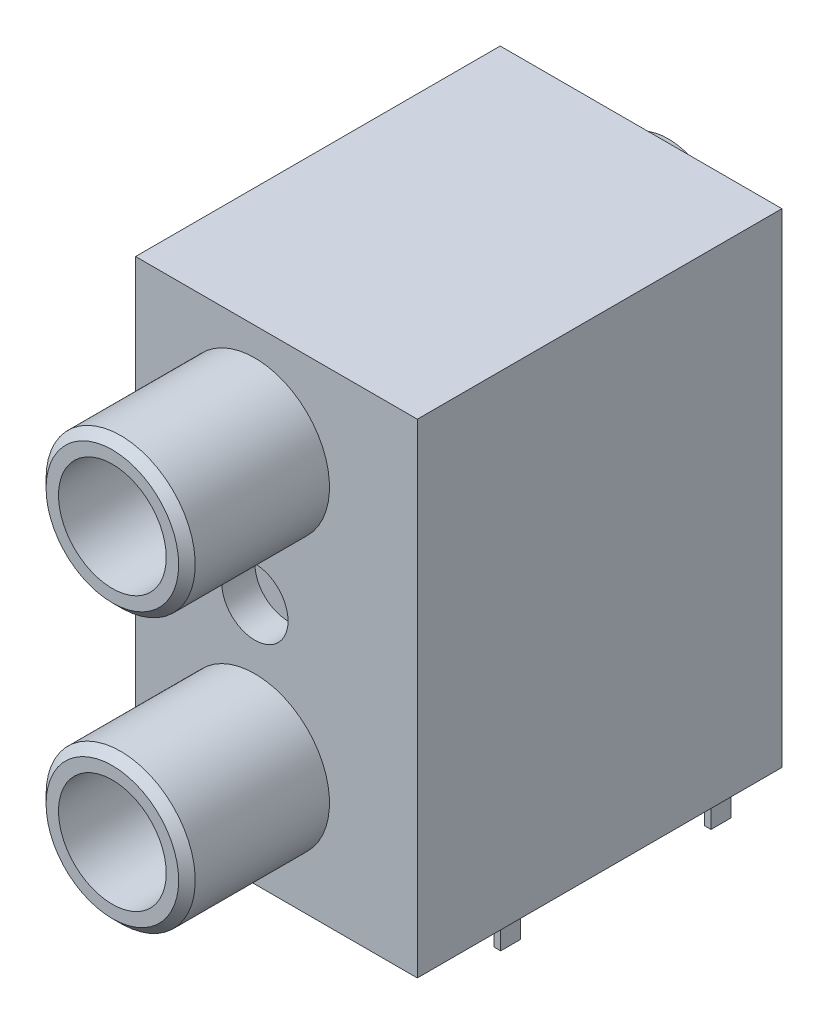
SolidWorks part; units mm, degrees
ref_plane "Front Plane" through (0, 0, 0) normal (0, 0, 1) x (1, 0, 0)
ref_plane "Top Plane" through (0, 0, 0) normal (0, 1, 0) x (1, 0, 0)
ref_plane "Right Plane" through (0, 0, 0) normal (1, 0, 0) x (0, 0, -1)
sketch "Sketch1" plane through (0, 0, 0) normal (0, 1, 0) x (1, 0, 0)
  line L1 (-15.8508, 12.6317) -> (1.1492, 12.6317)
  line L2 (-15.8508, 12.6317) -> (-15.8508, -9.3683)
  line L3 (-15.8508, -9.3683) -> (1.1492, -9.3683)
  line L4 (1.1492, 12.6317) -> (1.1492, -9.3683)
  dimension "D1" = 17
  dimension "D2" = 22
extrude "Boss-Extrude1" add sketch "Sketch1" along normal blind 29.2
sketch "Sketch3" plane through (0, 0, -12.6317) normal (0, 0, -1) x (-1, 0, 0)
  line L0 (-1.1492, 0) -> (15.8508, 0) construction
  line L1 (15.8508, 29.2) -> (15.8508, 0) construction
  circle A0 centre (8.6508, 6.5) radius 4
  dimension "D1" = 6.5
  dimension "D2" = 7.2
extrude "Boss-Extrude2" add sketch "Sketch3" along normal blind 2.94 draft 10
sketch "Sketch4" plane through (0, 0, 9.3683) normal (0, 0, 1) x (1, 0, 0)
  line L0 (-15.8508, 29.2) -> (-15.8508, 0) construction
  line L1 (-15.8508, 0) -> (1.1492, 0) construction
  circle A0 centre (-8.6508, 6.5) radius 4.5
  dimension "D1" = 7.2
  dimension "D2" = 6.5
extrude "Boss-Extrude3" add sketch "Sketch4" along normal blind 8.6
chamfer "Chamfer1" distance 0.5 angle 45 1 edges at (-4.1508, 6.5, 17.9683)
sketch "Sketch13" plane through (0, 0, 17.9683) normal (0, 0, 1) x (1, 0, 0)
  circle A0 centre (-8.6508, 6.5) radius 3.25
  dimension "D1" = 6.5
extrude "Cut-Extrude1" cut sketch "Sketch13" against normal blind 29
sketch "Sketch14" plane through (0, 0, 0) normal (0, -1, 0) x (1, 0, 0)
  line L0 (-8.1858, -12.6317) -> (-8.1858, 8.7283) construction
  line L1 (-14.1008, 5.3583) -> (-13.7008, 5.3583)
  line L2 (-14.1008, 5.3583) -> (-14.1008, 4.1583)
  line L3 (-14.1008, 4.1583) -> (-13.7008, 4.1583)
  line L4 (-13.7008, 5.3583) -> (-13.7008, 4.1583)
  line L5 (-2.2708, 5.3583) -> (-2.6708, 5.3583)
  line L6 (-9.5008, -1.3881) -> (-9.5008, 3.8102) construction
  line L7 (-2.2708, 5.3583) -> (-2.2708, 4.1583)
  line L8 (-2.6708, 5.3583) -> (-2.6708, 4.1583)
  line L9 (-2.2708, 4.1583) -> (-2.6708, 4.1583)
  line L10 (-2.2708, -7.3317) -> (-2.2708, -8.5317)
  line L11 (-2.2708, -8.5317) -> (-2.6708, -8.5317)
  line L12 (-2.6708, -7.3317) -> (-2.6708, -8.5317)
  line L13 (-2.2708, -7.3317) -> (-2.6708, -7.3317)
  line L14 (-14.1008, -7.3317) -> (-14.1008, -8.5317)
  line L15 (-14.1008, -8.5317) -> (-13.7008, -8.5317)
  line L16 (-13.7008, -7.3317) -> (-13.7008, -8.5317)
  line L17 (-15.8508, -12.6317) -> (-15.8508, 9.3683) construction
  line L18 (-15.8508, 9.3683) -> (1.1492, 9.3683) construction
  line L19 (-14.1008, -7.3317) -> (-13.7008, -7.3317)
  dimension "D1" = 1.2
  dimension "D2" = 0.4
  dimension "D3" = 2
  dimension "D4" = 5.515
  dimension "D5" = 6.35
  dimension "D6" = 4.2
  dimension "D7" = 4.01
extrude "Boss-Extrude4" add sketch "Sketch14" along normal blind 3.25
pattern_linear "LPattern1" count 2 spacing 16.5 along (0, 1, 0) of "Boss-Extrude2", "Boss-Extrude3", "Cut-Extrude1", "Chamfer1"
pattern_linear "LPattern2" count 2 spacing 3.17 along (0, 0, -1) count 2 spacing 1.27 along (1, 0, 0) skipping (0, 1), (1, 0) of "Boss-Extrude4"
sketch "Sketch15" plane through (0, 0, 9.3683) normal (0, 0, 1) x (1, 0, 0)
  line L0 (-15.8508, 0) -> (1.1492, 0) construction
  line L1 (-15.8508, 29.2) -> (-15.8508, 0) construction
  circle A0 centre (-8.6508, 14.75) radius 2
  dimension "D1" = 14.75
  dimension "D2" = 7.2
extrude "Cut-Extrude2" cut sketch "Sketch15" against normal blind 2
